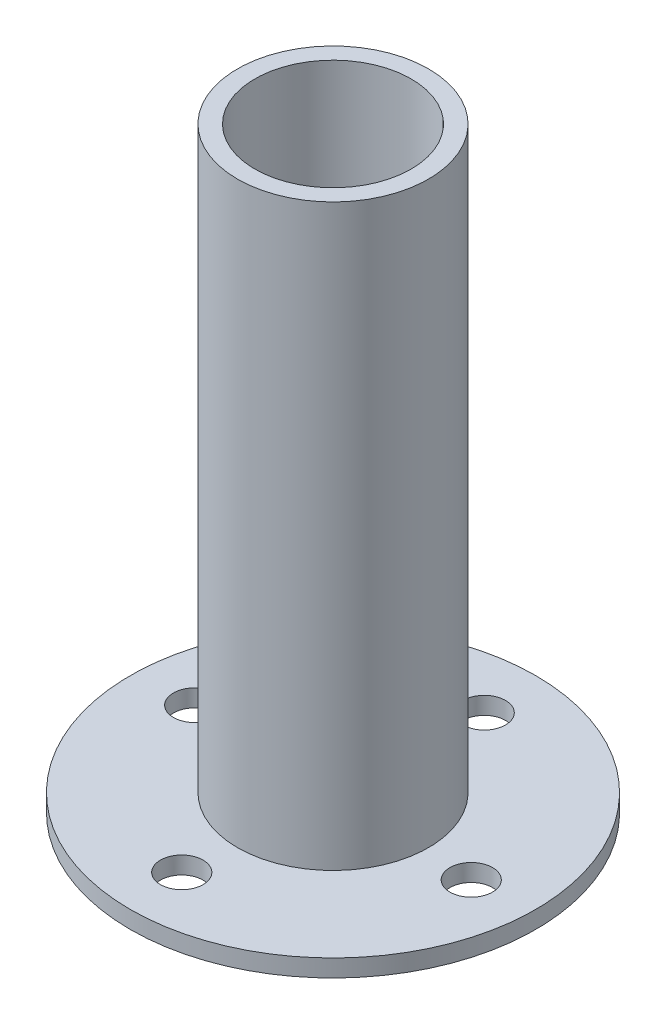
SolidWorks part; units mm, degrees
material "AISI 304"
ref_plane "Front" through (0, 0, 0) normal (0, 0, 1) x (1, 0, 0)
ref_plane "Top" through (0, 0, 0) normal (0, 1, 0) x (1, 0, 0)
ref_plane "Right" through (0, 0, 0) normal (1, 0, 0) x (0, 0, -1)
sketch "Sketch1" plane through (0, 0, 0) normal (0, 1, 0) x (1, 0, 0)
  circle A0 centre (0, 0) radius 35
  dimension "D1" = 70
extrude "Boss-Extrude1" add sketch "Sketch1" along normal blind 3
sketch "Sketch2" plane through (0, 3, 0) normal (0, 1, 0) x (1, 0, 0)
  circle A0 centre (0, 0) radius 14
  dimension "D1" = 28
extrude "Cut-Extrude1" cut sketch "Sketch2" against normal blind 6
sketch "Sketch3" plane through (0, 3, 0) normal (0, 1, 0) x (1, 0, 0)
  circle A0 centre (1.1195, 25) radius 3.6761
  dimension "D1" = 25
extrude "Cut-Extrude2" cut sketch "Sketch3" against normal blind 6
pattern_circular "CirPattern1" count 4 every 90 about axis through (0, 0, 0) along (0, 1, 0) of "Cut-Extrude2"
sketch "Sketch4" plane through (0, 3, 0) normal (0, 1, 0) x (1, 0, 0)
  circle A0 centre (0, 0) radius 16.5
  dimension "D1" = 33
extrude "Extrude-Thin1" add sketch "Sketch4" along normal blind 100 separate body thin thin type one direction reverse wall 3
